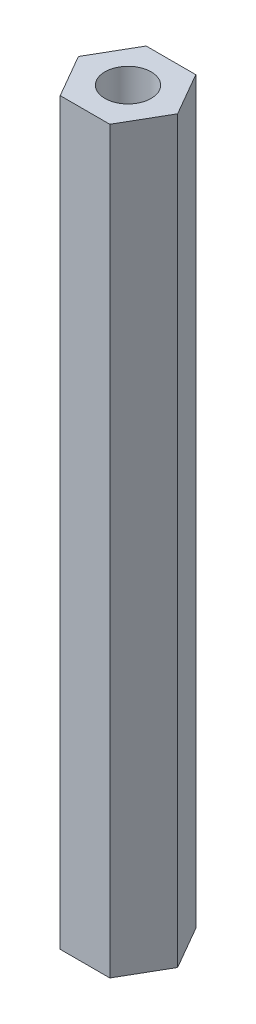
SolidWorks part; units mm, degrees
material "黄铜"
ref_plane "前视基准面" through (0, 0, 0) normal (0, 0, 1) x (1, 0, 0)
ref_plane "上视基准面" through (0, 0, 0) normal (0, 1, 0) x (1, 0, 0)
ref_plane "右视基准面" through (0, 0, 0) normal (1, 0, 0) x (0, 0, -1)
sketch "草图1" plane through (0, 0, 0) normal (0, 1, 0) x (1, 0, 0)
  line L1 (2.6847, 0) -> (1.3423, 2.325)
  line L2 (1.3423, 2.325) -> (-1.3423, 2.325)
  line L3 (-1.3423, 2.325) -> (-2.6847, 0)
  line L4 (-2.6847, 0) -> (-1.3423, -2.325)
  line L5 (-1.3423, -2.325) -> (1.3423, -2.325)
  line L6 (1.3423, -2.325) -> (2.6847, 0)
  circle A0 centre (0, 0) radius 2.325 construction
  dimension "D1" = 4.65
extrude "凸台-拉伸1" add sketch "草图1" along normal mid plane 40
hole_wizard "M3 螺纹孔1" positions "草图3" profile "草图2" tap size "M3" standard "GB"
sketch "草图3" plane through (0, -20, 0) normal (0, -1, 0) x (-1, 0, 0)
  point P0 (0, 0)
sketch "草图2" plane through (0, -20, 0) normal (1, 0, 0) x (0, 0, -1)
  line L0 (0, 0) -> (0, 8.2511)
  line L1 (0, 8.2511) -> (1.25, 7.5)
  line L2 (1.25, 7.5) -> (1.25, 0)
  line L5 (1.25, 0) -> (0, 0)
  line L10 (0, 8.2511) -> (-1.25, 7.5) construction
  line L11 (0, -6.35) -> (0, 107.95) construction
  dimension "螺纹孔钻头直径" = 2.5
  dimension "螺纹孔钻头深度" = 7.5
  dimension "导头角度" = 118
cosmetic thread "孔螺蚊线1" parameters "D1"=5, "D2"=3
mirror "镜向1" about plane through (0, 0, 0) normal (0, 1, 0) of "M3 螺纹孔1"
equation "\"高度\"= 5"
equation "\"对边距离\"= 4.65"
equation "\"D1@草图1\"=\"对边距离\""
equation "\"D1@凸台-拉伸1\"=\"高度\""
